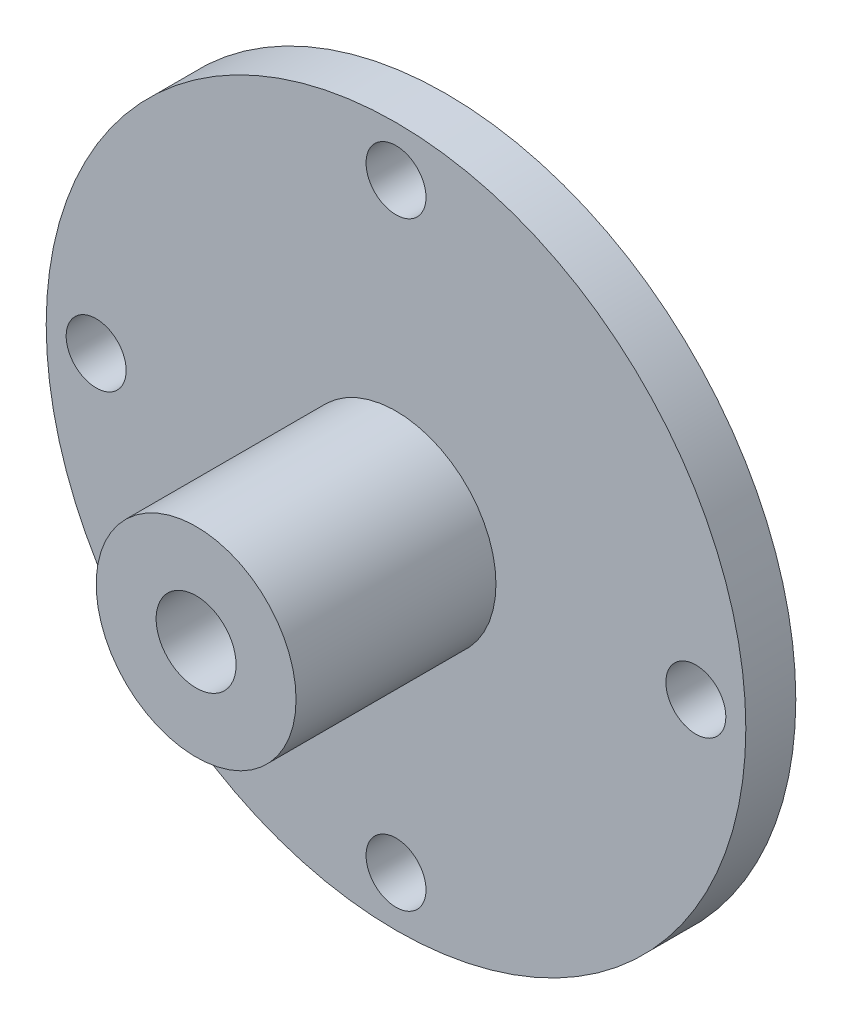
SolidWorks part; units mm, degrees
material "1060 Alloy"
ref_plane "Front Plane" through (0, 0, 0) normal (0, 0, 1) x (1, 0, 0)
ref_plane "Top Plane" through (0, 0, 0) normal (0, 1, 0) x (1, 0, 0)
ref_plane "Right Plane" through (0, 0, 0) normal (1, 0, 0) x (0, 0, -1)
sketch "Sketch1" plane through (0, 0, 0) normal (0, 0, 1) x (1, 0, 0)
  circle A0 centre (0, 0) radius 35
extrude "Boss-Extrude1" add sketch "Sketch1" along normal blind 5
sketch "Sketch4" plane through (0, 0, 5) normal (0, 0, 1) x (1, 0, 0)
  circle A1 centre (0, 30) radius 3
  circle A2 centre (30, 0) radius 3
  circle A3 centre (0, -30) radius 3
  circle A4 centre (-30, 0) radius 3
  point P14 (0, 0)
  dimension "D1" = 4
extrude "Cut-Extrude1" cut sketch "Sketch4" against normal blind 5
sketch "Sketch5" plane through (0, 0, 5) normal (0, 0, 1) x (1, 0, 0)
  circle A0 centre (0, 0) radius 10
extrude "Boss-Extrude2" add sketch "Sketch5" along normal blind 20
sketch "Sketch6" plane through (0, 0, 25) normal (0, 0, 1) x (1, 0, 0)
  circle A0 centre (0, 0) radius 4
extrude "Cut-Extrude2" cut sketch "Sketch6" against normal blind 20
